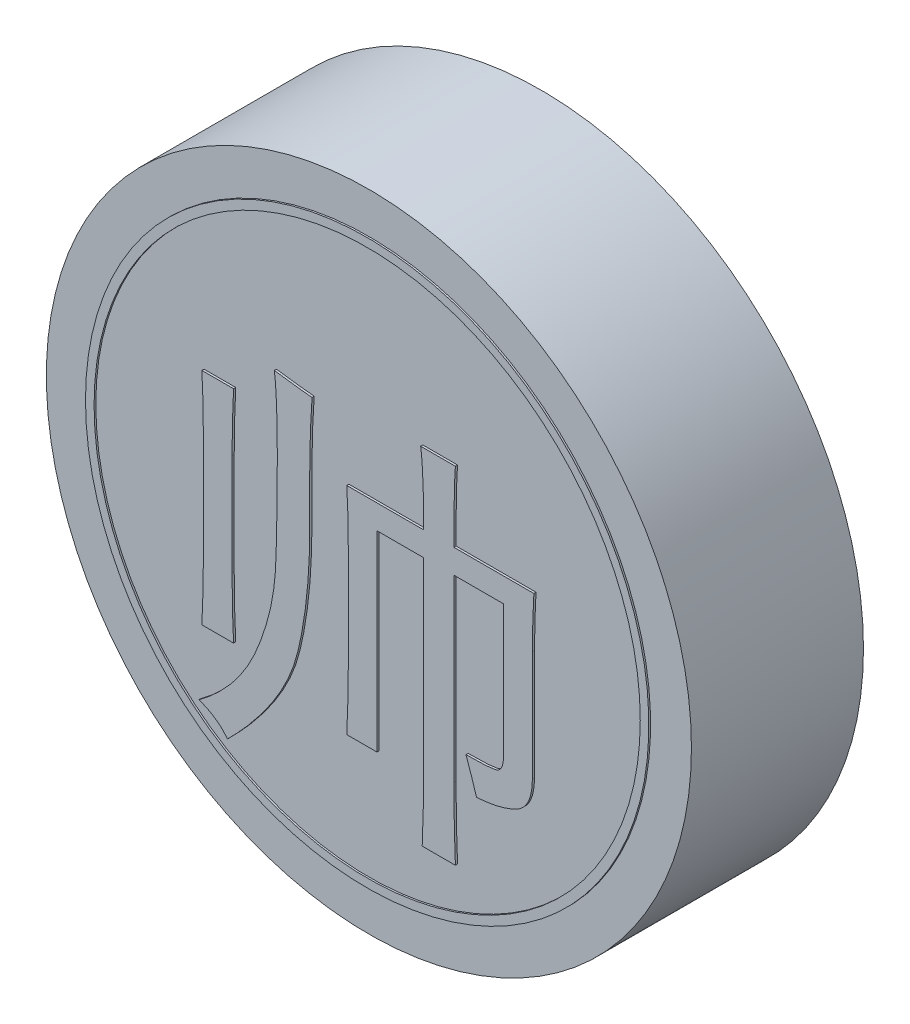
SolidWorks part; units mm, degrees
ref_plane "前视基准面" through (0, 0, 0) normal (0, 0, 1) x (1, 0, 0)
ref_plane "上视基准面" through (0, 0, 0) normal (0, 1, 0) x (1, 0, 0)
ref_plane "右视基准面" through (0, 0, 0) normal (1, 0, 0) x (0, 0, -1)
other "Configuration Table"
sketch "草图1" plane through (0, 0, 0) normal (0, 0, 1) x (1, 0, 0)
  circle A0 centre (0, 0) radius 15
  dimension "D1" = 30
extrude "Diameter30_Height8" add sketch "草图1" against normal blind 8
sketch "草图2" plane through (0, 0, 0) normal (0, 0, 1) x (1, 0, 0)
  text T0 "帅" font "SimHei" height 12
extrude "Character_帅" add sketch "草图2" along normal blind 0.1
sketch "草图3" plane through (0, 0, 0) normal (0, 0, 1) x (1, 0, 0)
  circle A0 centre (0, 0) radius 13.1
  circle A1 centre (0, 0) radius 12.7
extrude "Ink_ring" add sketch "草图3" along normal blind 0.08
